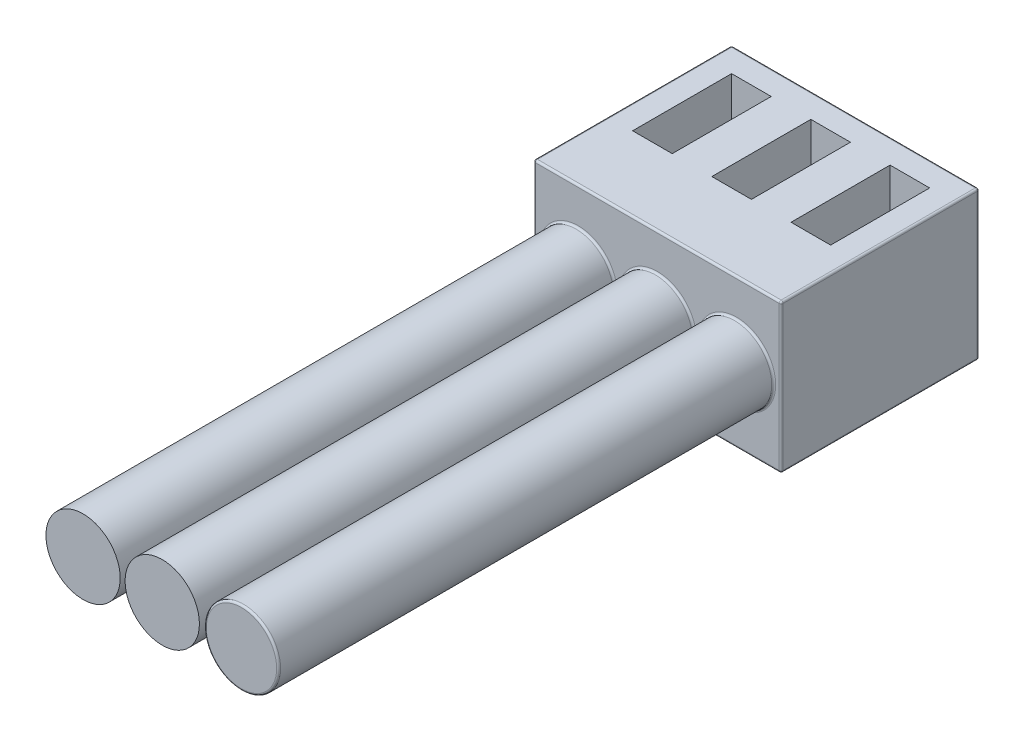
SolidWorks part; units mm, degrees
ref_plane "前基準面" through (0, 0, 0) normal (0, 0, 1) x (1, 0, 0)
ref_plane "上基準面" through (0, 0, 0) normal (0, 1, 0) x (1, 0, 0)
ref_plane "右基準面" through (0, 0, 0) normal (1, 0, 0) x (0, 0, -1)
sketch "草圖1" plane through (0, 0, 0) normal (0, 0, 1) x (1, 0, 0)
  line L1 (-2.4413, 1.3542) -> (2.5587, 1.3542)
  line L2 (-2.4413, 1.3542) -> (-2.4413, -1.6458)
  line L3 (-2.4413, -1.6458) -> (2.5587, -1.6458)
  line L4 (2.5587, 1.3542) -> (2.5587, -1.6458)
  dimension "D1" = 5
  dimension "D2" = 3
extrude "填料-伸長1" add sketch "草圖1" along normal blind 4
sketch "草圖2" plane through (0, 0, 4) normal (0, 0, 1) x (1, 0, 0)
  line L1 (2.5587, 1.3542) -> (-2.4413, 1.3542) construction
  line L2 (-1.5413, -0.1458) -> (-0.0413, -0.1458) construction
  line L3 (-1.5413, -0.1458) -> (0.0587, -0.1458) construction
  line L4 (-2.4413, 1.3542) -> (-2.4413, -1.6458) construction
  circle A0 centre (-1.5413, -0.1458) radius 0.75
  circle A3 centre (0.0587, -0.1458) radius 0.75
  circle A4 centre (1.6587, -0.1458) radius 0.75
  point P14 (0, 0)
  dimension "D1" = 3
  dimension "D2" = 1.5
  dimension "D3" = 1.5
  dimension "D4" = 0.9
extrude "填料-伸長5" add sketch "草圖2" along normal blind 10 contours A0 | A3 | A4
sketch "草圖4" plane through (0, 1.3542, 0) normal (0, 1, 0) x (1, 0, 0)
  line L0 (2.5587, -4) -> (-2.4413, -4) construction
  line L1 (2.0587, -2.5) -> (1.2587, -2.5)
  line L2 (2.0587, -2.5) -> (2.0587, -0.5)
  line L3 (2.0587, -0.5) -> (1.2587, -0.5)
  line L4 (1.2587, -2.5) -> (1.2587, -0.5)
  line L5 (0.4587, -2.5) -> (0.4587, -0.5)
  line L6 (0.4587, -2.5) -> (-0.3413, -2.5)
  line L7 (-0.3413, -2.5) -> (-0.3413, -0.5)
  line L8 (0.4587, -0.5) -> (-0.3413, -0.5)
  line L9 (-1.1413, -2.5) -> (-1.1413, -0.5)
  line L10 (-1.1413, -2.5) -> (-1.9413, -2.5)
  line L11 (-1.9413, -2.5) -> (-1.9413, -0.5)
  line L12 (-1.1413, -0.5) -> (-1.9413, -0.5)
  line L13 (2.0587, -2.5) -> (0.4587, -2.5) construction
  line L14 (2.5587, -4) -> (2.5587, 0) construction
  dimension "D1" = 0.8
  dimension "D2" = 2
  dimension "D3" = 1.5
  dimension "D5" = 1.6
  dimension "D6" = 0.5
  dimension "D4" = 3
extrude "除料-伸長1" cut sketch "草圖4" against normal blind 1
sketch "草圖5" plane through (0, 0, 0) normal (0, 0, -1) x (-1, 0, 0)
  line L0 (-2.5587, 1.3542) -> (2.4413, 1.3542) construction
  line L1 (-1.9587, 0.1542) -> (-1.3587, 0.1542)
  line L2 (-1.9587, 0.1542) -> (-1.9587, -0.4458)
  line L3 (-1.9587, -0.4458) -> (-1.3587, -0.4458)
  line L4 (-1.3587, 0.1542) -> (-1.3587, -0.4458)
  line L5 (2.4413, -1.6458) -> (-2.5587, -1.6458) construction
  line L6 (-0.3587, 0.1542) -> (-0.3587, -0.4458)
  line L7 (-0.3587, 0.1542) -> (0.2413, 0.1542)
  line L8 (0.2413, 0.1542) -> (0.2413, -0.4458)
  line L9 (-0.3587, -0.4458) -> (0.2413, -0.4458)
  line L10 (1.2413, 0.1542) -> (1.2413, -0.4458)
  line L11 (1.2413, 0.1542) -> (1.8413, 0.1542)
  line L12 (1.8413, 0.1542) -> (1.8413, -0.4458)
  line L13 (1.2413, -0.4458) -> (1.8413, -0.4458)
  line L14 (-1.9587, 0.1542) -> (-0.3587, 0.1542) construction
  line L15 (-2.5587, -1.6458) -> (-2.5587, 1.3542) construction
  dimension "D1" = 1.2
  dimension "D2" = 1.2
  dimension "D3" = 0.6
  dimension "D5" = 1.6
  dimension "D6" = 0.6
  dimension "D4" = 3
extrude "除料-伸長2" cut sketch "草圖5" against normal blind 2
fillet "圓角1" radius 0.04 16 edges at (2.4087, -0.1458, 4) (2.4087, -0.1458, 14) (2.5587, -0.1458, 4) (0.0587, 1.3542, 4) (2.5587, -0.1458, 0) (0.0587, 1.3542, 0) (-2.4413, -0.1458, 0) (-2.4413, -0.1458, 4) (0.0587, -1.6458, 0) (0.0587, -1.6458, 4) (-0.7913, -0.1458, 4) (0.8087, -0.1458, 4) (2.5587, -1.6458, 2) (2.5587, 1.3542, 2) (-2.4413, -1.6458, 2) (-2.4413, 1.3542, 2)
